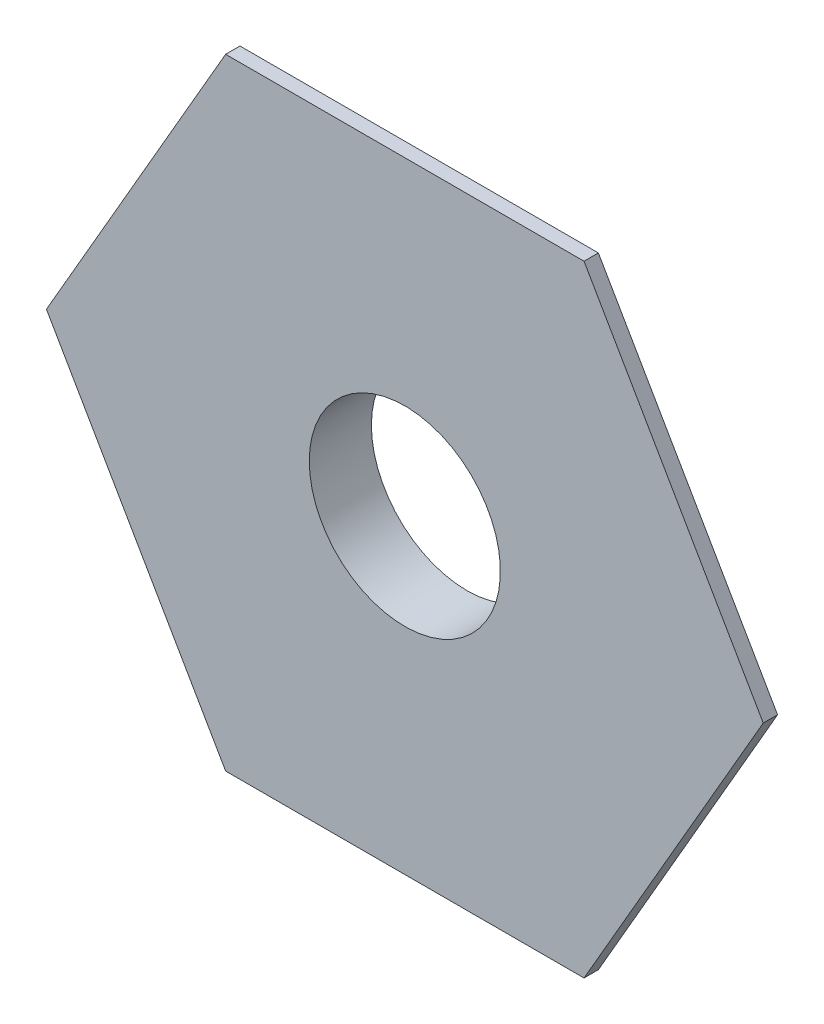
SolidWorks part; units mm, degrees
ref_plane "前视基准面" through (0, 0, 0) normal (0, 0, 1) x (1, 0, 0)
ref_plane "上视基准面" through (0, 0, 0) normal (0, 1, 0) x (1, 0, 0)
ref_plane "右视基准面" through (0, 0, 0) normal (1, 0, 0) x (0, 0, -1)
other "Configuration Table"
sketch "草图1" plane through (0, 0, 0) normal (0, 0, 1) x (1, 0, 0)
  circle A0 centre (0, 0) radius 37.5
  dimension "D1" = 75
extrude "凸台-拉伸1" add sketch "草图1" along normal blind 3
sketch "草图2" plane through (0, 0, 0) normal (0, 0, -1) x (-1, 0, 0)
  circle A0 centre (0, 0) radius 25 construction
  circle A1 centre (0, 0) radius 25
extrude "切除-拉伸1" cut sketch "草图2" against normal blind 3
sketch "草图3" plane through (0, 0, 3) normal (0, 0, 1) x (1, 0, 0)
  line L0 (0, -30) -> (0, 0) construction
  circle A0 centre (0, -30) radius 1.5
  dimension "D1" = 3
  dimension "D2" = 30
extrude "切除-拉伸2" cut sketch "草图3" against normal blind 13
pattern_circular "阵列(圆周)1" count 8 over 360 about axis through (0, 0, 0) along (0, 0, 1) of "切除-拉伸2"
sketch "草图4" plane through (0, 0, 3) normal (0, 0, 1) x (1, 0, 0)
  circle A0 centre (0, 0) radius 20
  circle A1 centre (0, 0) radius 25 construction
  circle A2 centre (0, 0) radius 25
extrude "凸台-拉伸2" add sketch "草图4" against normal blind 10 and the other way blind 5
sketch "草图6" plane through (0, 0, 3) normal (0, 0, 1) x (1, 0, 0)
  line L1 (100, 75) -> (-100, 75)
  line L2 (100, 75) -> (100, -75)
  line L3 (100, -75) -> (-100, -75)
  line L4 (-100, 75) -> (-100, -75)
  line L5 (100, 75) -> (-100, -75) construction
  line L6 (100, -75) -> (-100, 75) construction
  point P0 (0, 0)
  dimension "D1" = 150
  dimension "D2" = 200
sketch "草图7" plane through (0, 0, 8) normal (0, 0, 1) x (1, 0, 0)
  line L0 (100, 75) -> (-100, -75) construction
  circle A0 centre (0, 0) radius 28.1953
  dimension "D1" = 56.3906
extrude "切除-拉伸3" cut sketch "草图7" against normal up to surface (5 mm away) up to face at (-30, -1.5, 3)
sketch "草图8" plane through (0, 0, 3) normal (0, 0, 1) x (1, 0, 0)
  line L0 (100, -75) -> (-100, 75) construction
  line L1 (37.5, 64.9519) -> (-37.5, 64.9519)
  line L2 (-37.5, 64.9519) -> (-75, 0)
  line L3 (-75, 0) -> (-37.5, -64.9519)
  line L4 (-37.5, -64.9519) -> (37.5, -64.9519)
  line L5 (37.5, -64.9519) -> (75, 0)
  line L6 (75, 0) -> (37.5, 64.9519)
  circle A0 centre (0, 0) radius 64.9519 construction
  dimension "D1" = 75
extrude "凸台-拉伸3" add sketch "草图8" along normal blind 3
sketch "草图9" plane through (0, 0, 3) normal (0, 0, -1) x (-1, 0, 0)
  circle A1 centre (0, 0) radius 20
  circle A2 centre (0, 0) radius 20
  dimension "D1" = 0
extrude "切除-拉伸4" cut sketch "草图9" against normal through all both and the other way through all
